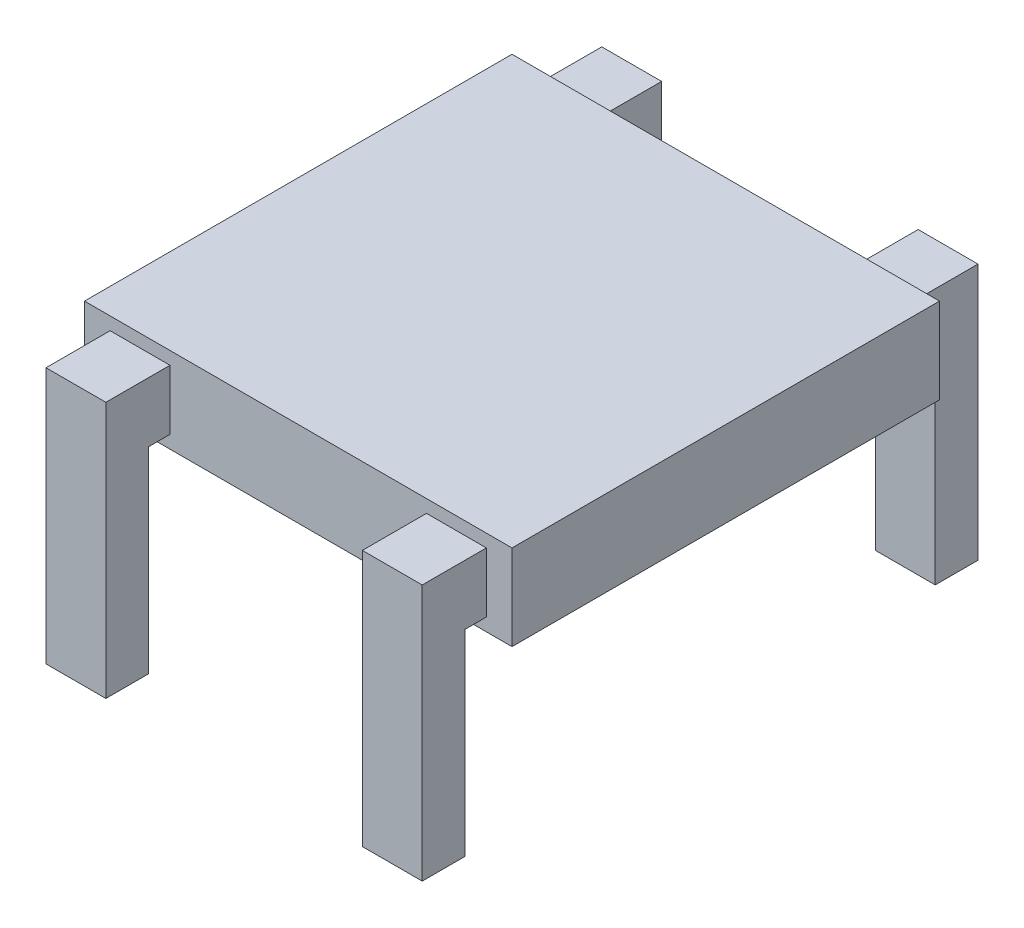
SolidWorks part; units mm, degrees
ref_plane "Front Plane" through (0, 0, 0) normal (0, 0, 1) x (1, 0, 0)
ref_plane "Top Plane" through (0, 0, 0) normal (0, 1, 0) x (1, 0, 0)
ref_plane "Right Plane" through (0, 0, 0) normal (1, 0, 0) x (0, 0, -1)
sketch "Sketch1" plane through (0, 0, 0) normal (0, 1, 0) x (1, 0, 0)
  line L1 (2.5, -2.5) -> (-2.5, -2.5)
  line L2 (2.5, -2.5) -> (2.5, 2.5)
  line L3 (2.5, 2.5) -> (-2.5, 2.5)
  line L4 (-2.5, -2.5) -> (-2.5, 2.5)
  line L5 (2.5, -2.5) -> (-2.5, 2.5) construction
  line L6 (2.5, 2.5) -> (-2.5, -2.5) construction
  point P0 (0, 0)
  dimension "D1" = 5
  dimension "D2" = 5
extrude "Boss-Extrude1" add sketch "Sketch1" along normal blind 1
sketch "Sketch2" plane through (0, 0, 2.5) normal (0, 0, 1) x (1, 0, 0)
  line L0 (-2.5, 0.5) -> (2.5, 0.5) construction
  line L1 (-2.5, 1) -> (-2.5, 0) construction
  line L2 (2.5, 1) -> (2.5, 0) construction
  line L3 (0, 1) -> (0, -0.1384) construction
  line L4 (-1.5, 0.15) -> (-2.2, 0.15)
  line L5 (-1.5, 0.15) -> (-1.5, 0.85)
  line L6 (-1.5, 0.85) -> (-2.2, 0.85)
  line L7 (-2.2, 0.15) -> (-2.2, 0.85)
  line L8 (-1.5, 0.15) -> (-2.2, 0.85) construction
  line L9 (-1.5, 0.85) -> (-2.2, 0.15) construction
  line L10 (-2.5, 1) -> (2.5, 1) construction
  line L11 (2.2, 0.15) -> (2.2, 0.85)
  line L12 (1.5, 0.15) -> (2.2, 0.15)
  line L13 (1.5, 0.15) -> (1.5, 0.85)
  line L14 (1.5, 0.85) -> (2.2, 0.85)
  point P6 (-1.85, 0.5)
  dimension "D1" = 0.7
  dimension "D2" = 0.7
  dimension "D3" = 0.3
extrude "Boss-Extrude2" add sketch "Sketch2" along normal blind 0.5
sketch "Sketch7" plane through (0, 0.85, 0) normal (0, 1, 0) x (1, 0, 0)
  line L0 (-1.5, -3) -> (-2.2, -3) construction
  line L1 (-1.5, -3.25) -> (-2.2, -3.25)
  line L2 (-1.5, -3.25) -> (-1.5, -2.75)
  line L3 (-1.5, -2.75) -> (-2.2, -2.75)
  line L4 (-2.2, -3.25) -> (-2.2, -2.75)
  line L5 (-1.5, -3.25) -> (-2.2, -2.75) construction
  line L6 (-1.5, -2.75) -> (-2.2, -3.25) construction
  line L7 (-2.2, -3) -> (-2.2, -2.5) construction
  line L8 (2.2, -3) -> (1.5, -3) construction
  line L9 (2.2, -3.25) -> (1.5, -3.25)
  line L10 (2.2, -3.25) -> (2.2, -2.75)
  line L11 (2.2, -2.75) -> (1.5, -2.75)
  line L12 (1.5, -3.25) -> (1.5, -2.75)
  line L13 (2.2, -3.25) -> (1.5, -2.75) construction
  line L14 (2.2, -2.75) -> (1.5, -3.25) construction
  line L15 (1.5, -3) -> (1.5, -2.5) construction
  point P0 (-1.85, -3)
  point P9 (1.85, -3)
  dimension "D1" = 0.5
  dimension "D2" = 0.5
extrude "Boss-Extrude3" add sketch "Sketch7" against normal blind 3
sketch "Sketch8" plane through (0, 0, -2.5) normal (0, 0, -1) x (-1, 0, 0)
  line L0 (-2.5, 0.5) -> (2.5, 0.5) construction
  line L1 (-2.5, 1) -> (-2.5, 0) construction
  line L2 (2.5, 1) -> (2.5, 0) construction
  line L3 (0, 1.1124) -> (0, -0.4605) construction
  line L4 (-1.5, 0.15) -> (-2.2, 0.15)
  line L5 (-1.5, 0.15) -> (-1.5, 0.85)
  line L6 (-1.5, 0.85) -> (-2.2, 0.85)
  line L7 (-2.2, 0.15) -> (-2.2, 0.85)
  line L8 (-1.5, 0.15) -> (-2.2, 0.85) construction
  line L9 (-1.5, 0.85) -> (-2.2, 0.15) construction
  line L10 (1.5, 0.15) -> (1.5, 0.85)
  line L11 (1.5, 0.15) -> (2.2, 0.15)
  line L12 (2.2, 0.15) -> (2.2, 0.85)
  line L13 (1.5, 0.85) -> (2.2, 0.85)
  point P6 (-1.85, 0.5)
  dimension "D1" = 0.3
  dimension "D2" = 0.7
  dimension "D3" = 0.7
extrude "Boss-Extrude4" add sketch "Sketch8" along normal blind 0.5
sketch "Sketch9" plane through (0, 0.85, 0) normal (0, 1, 0) x (1, 0, 0)
  line L0 (-2.2, 3) -> (-1.5, 3) construction
  line L1 (-1.5, 2.75) -> (-2.2, 2.75)
  line L2 (-1.5, 2.75) -> (-1.5, 3.25)
  line L3 (-1.5, 3.25) -> (-2.2, 3.25)
  line L4 (-2.2, 2.75) -> (-2.2, 3.25)
  line L5 (-1.5, 2.75) -> (-2.2, 3.25) construction
  line L6 (-1.5, 3.25) -> (-2.2, 2.75) construction
  line L7 (1.5, 3) -> (2.2, 3) construction
  line L8 (2.2, 2.75) -> (1.5, 2.75)
  line L9 (2.2, 2.75) -> (2.2, 3.25)
  line L10 (2.2, 3.25) -> (1.5, 3.25)
  line L11 (1.5, 2.75) -> (1.5, 3.25)
  line L12 (2.2, 2.75) -> (1.5, 3.25) construction
  line L13 (2.2, 3.25) -> (1.5, 2.75) construction
  point P0 (-1.85, 3)
  point P7 (1.85, 3)
  dimension "D1" = 0.5
  dimension "D2" = 0.5
extrude "Boss-Extrude5" add sketch "Sketch9" against normal blind 3
